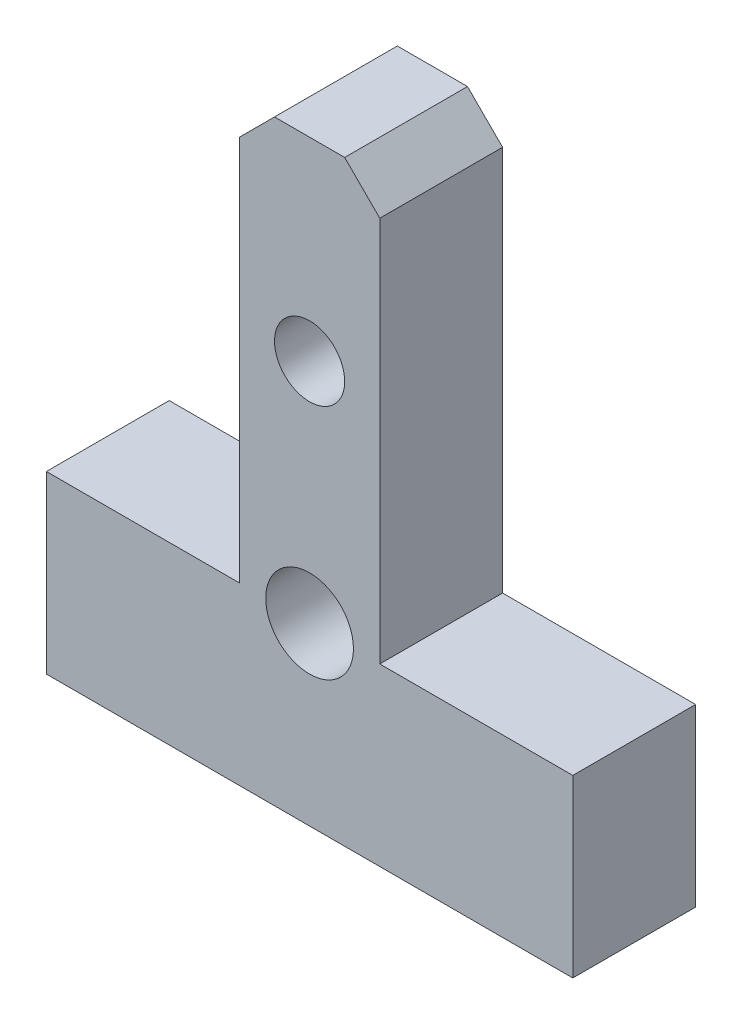
SolidWorks part; units mm, degrees
ref_plane "Спереди" through (0, 0, 0) normal (0, 0, 1) x (1, 0, 0)
ref_plane "Сверху" through (0, 0, 0) normal (0, 1, 0) x (1, 0, 0)
ref_plane "Справа" through (0, 0, 0) normal (1, 0, 0) x (0, 0, -1)
sketch "Эскиз1" plane through (0, 0, 0) normal (0, 0, 1) x (1, 0, 0)
  line L0 (0, -11.5567) -> (0, -51.7001) construction
  line L2 (-15, -1.146) -> (-15, -11.146)
  line L3 (4, 9.354) -> (-4, 9.354)
  line L4 (4, -1.146) -> (4, 9.354)
  line L5 (-15, -1.146) -> (-4, -1.146)
  line L6 (-4, -1.146) -> (-4, 9.354)
  line L8 (15, -1.146) -> (4, -1.146)
  line L9 (15, -1.146) -> (15, -11.146)
  line L10 (-15, -11.146) -> (15, -11.146)
  dimension "D1" = 15
  dimension "D2" = 15
  dimension "D3" = 4
  dimension "D4" = 4
extrude "Вытянуть1" add sketch "Эскиз1" along normal blind 7
sketch "Эскиз3" plane through (0, 9.354, 0) normal (0, 1, 0) x (1, 0, 0)
  line L1 (-4, 0) -> (4, 0)
  line L2 (-4, 0) -> (-4, -7)
  line L3 (-4, -7) -> (4, -7)
  line L4 (4, 0) -> (4, -7)
  line L5 (-4, 0) -> (4, -7) construction
  line L6 (-4, -7) -> (4, 0) construction
  point P0 (0, -3.5)
extrude "Вытянуть3" add sketch "Эскиз3" along normal blind 13.5
sketch "Эскиз2" plane through (0, 0, 7) normal (0, 0, 1) x (1, 0, 0)
  circle A0 centre (0, -1.146) radius 2.5
  circle A1 centre (0, 11.7946) radius 2
extrude "Вытянуть2" cut sketch "Эскиз2" against normal through all
chamfer "Фаска1" distance 2 angle 45 2 edges at (-4, 22.854, 3.5) (4, 22.854, 3.5)
